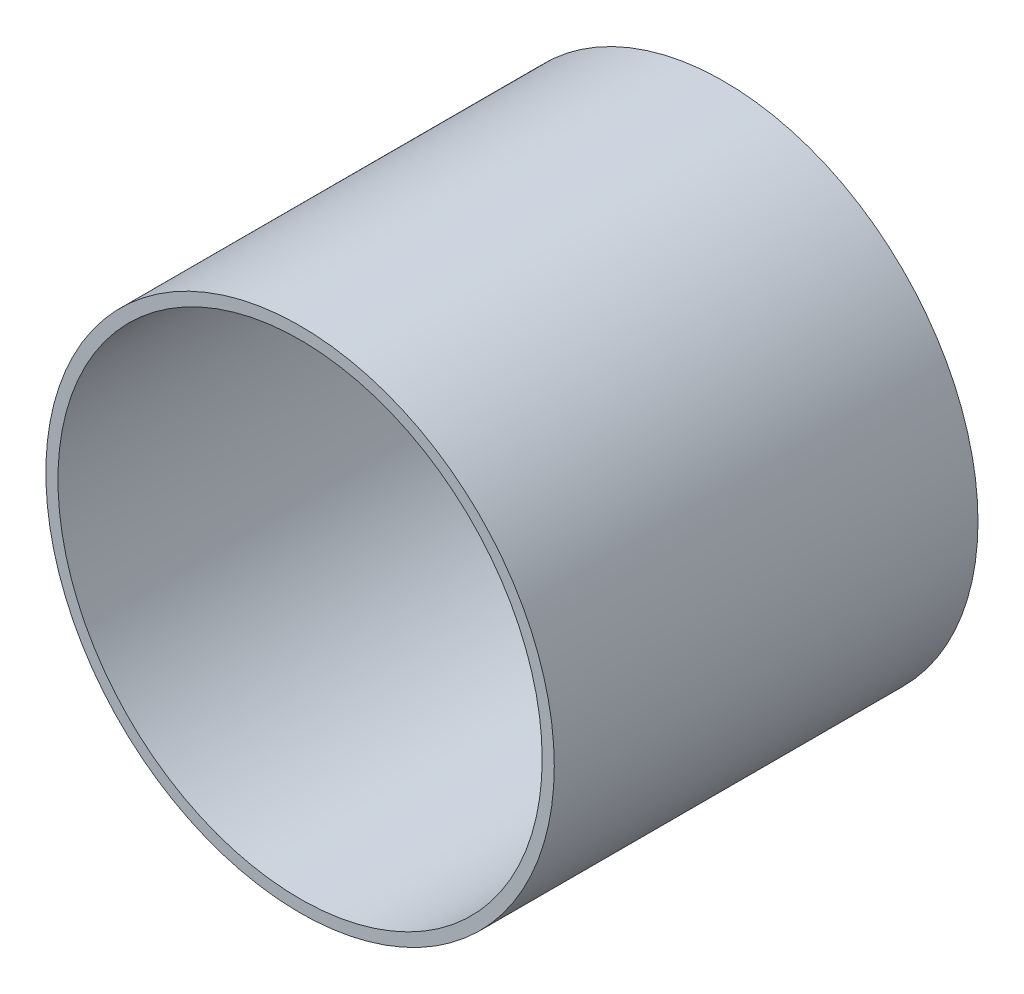
SolidWorks part; units mm, degrees
material "ABS"
ref_plane "Front Plane" through (0, 0, 0) normal (0, 0, 1) x (1, 0, 0)
ref_plane "Top Plane" through (0, 0, 0) normal (0, 1, 0) x (1, 0, 0)
ref_plane "Right Plane" through (0, 0, 0) normal (1, 0, 0) x (0, 0, -1)
sketch "Extrude sketch 1" plane through (0, 0, 0) normal (0, 0, 1) x (1, 0, 0)
  circle A0 centre (0, 0) radius 16.8
  circle A1 centre (0, 0) radius 16
  dimension "D1" = 32
  dimension "D2" = 33.6
extrude "Extrude 1" add sketch "Extrude sketch 1" along normal blind 28 from offset 200 separate body
